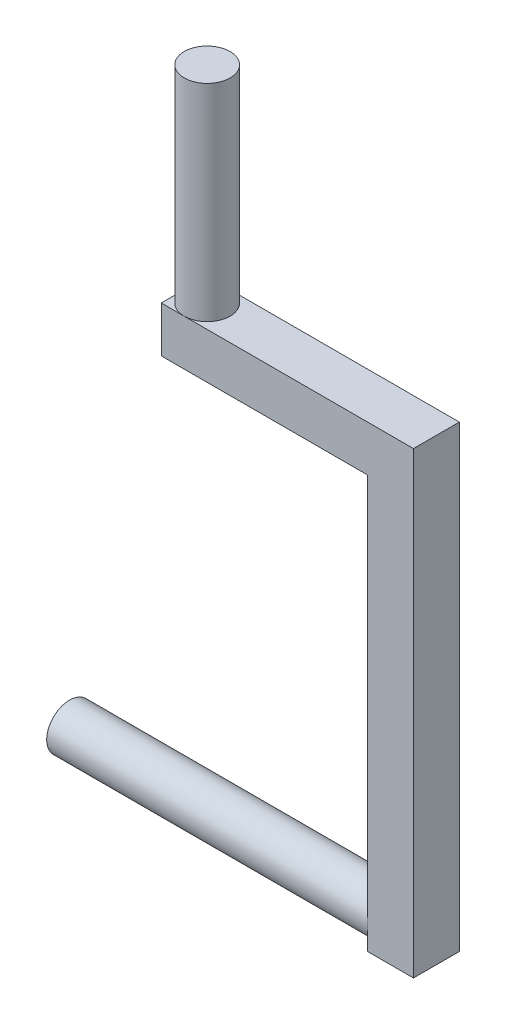
SolidWorks part; units mm, degrees
ref_plane "Front Plane" through (0, 0, 0) normal (0, 0, 1) x (1, 0, 0)
ref_plane "Top Plane" through (0, 0, 0) normal (0, 1, 0) x (1, 0, 0)
ref_plane "Right Plane" through (0, 0, 0) normal (1, 0, 0) x (0, 0, -1)
sketch "Sketch2" plane through (0, 0, 0) normal (0, 1, 0) x (1, 0, 0)
  circle A0 centre (0, 0) radius 6.35
extrude "Boss-Extrude1" add sketch "Sketch2" against normal blind 57.15
sketch "Sketch4" plane through (0, -57.15, 0) normal (0, -1, 0) x (1, 0, 0)
  line L0 (0, 0) -> (57.15, 0) construction
  line L2 (63.5, -6.35) -> (-6.35, -6.35)
  line L3 (63.5, -6.35) -> (63.5, 6.35)
  line L4 (63.5, 6.35) -> (-6.35, 6.35)
  line L5 (-6.35, -6.35) -> (-6.35, 6.35)
  line L6 (63.5, -6.35) -> (-6.35, 6.35) construction
  line L7 (63.5, 6.35) -> (-6.35, -6.35) construction
  point P0 (0, 0)
  point P5 (28.575, 0)
  point P10 (0, 0)
  dimension "D1" = 57.15
  dimension "D2" = 69.85
  dimension "D3" = 12.7
extrude "Boss-Extrude6" add sketch "Sketch4" along normal blind 12.7 contours L3 L4 L5 L2
sketch "Sketch7" plane through (0, -69.85, 0) normal (0, -1, 0) x (1, 0, 0)
  line L0 (63.5, -6.35) -> (63.5, 6.35) construction
  line L1 (63.5, 6.35) -> (-6.35, 6.35) construction
  point P0 (57.15, 0)
  dimension "D1" = 6.35
  dimension "D2" = 6.35
sketch "Sketch8" plane through (0, -69.85, 0) normal (0, -1, 0) x (1, 0, 0)
  line L0 (63.5, 6.35) -> (-6.35, 6.35) construction
  line L1 (63.5, -6.35) -> (50.8, -6.35)
  line L2 (63.5, -6.35) -> (63.5, 6.35)
  line L3 (63.5, 6.35) -> (50.8, 6.35)
  line L4 (50.8, -6.35) -> (50.8, 6.35)
  line L5 (63.5, -6.35) -> (50.8, 6.35) construction
  line L6 (63.5, 6.35) -> (50.8, -6.35) construction
  point P0 (57.15, 0)
  dimension "D1" = 12.7
extrude "Boss-Extrude7" add sketch "Sketch8" along normal blind 114.3
sketch "Sketch9" plane through (50.8, 0, 0) normal (-1, 0, 0) x (0, 0, 1)
  line L0 (6.35, -184.15) -> (-6.35, -184.15) construction
  line L1 (6.35, -184.15) -> (6.35, -69.85) construction
  circle A0 centre (0, -177.8) radius 6.35
  point P0 (0, -177.8)
  dimension "D1" = 6.35
  dimension "D2" = 6.35
extrude "Boss-Extrude8" add sketch "Sketch9" along normal blind 88.9
